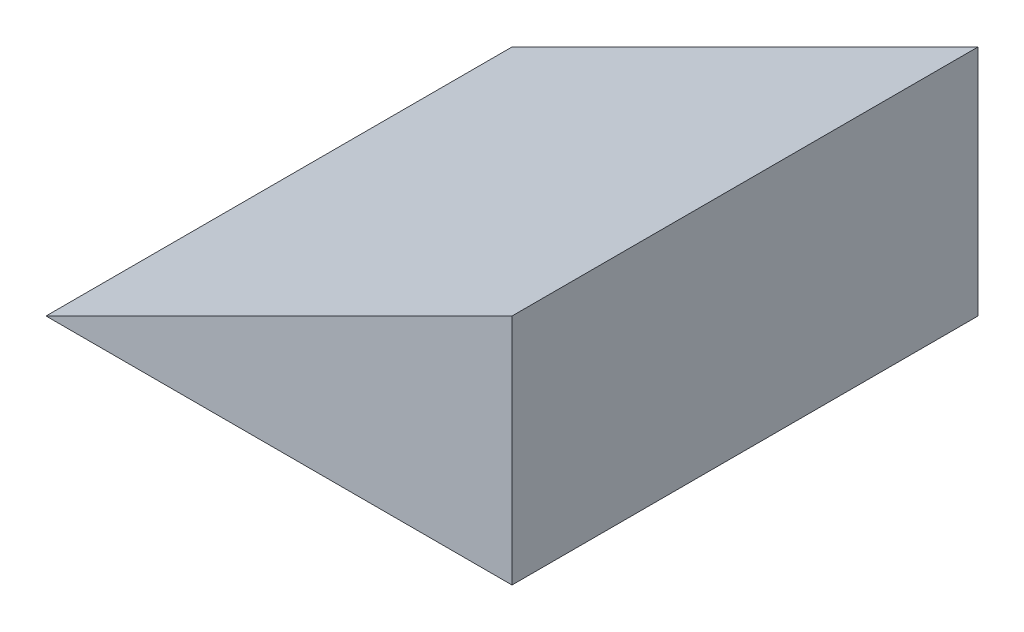
SolidWorks part; units mm, degrees
ref_plane "Płaszczyzna przednia" through (0, 0, 0) normal (0, 0, 1) x (1, 0, 0)
ref_plane "Płaszczyzna górna" through (0, 0, 0) normal (0, 1, 0) x (1, 0, 0)
ref_plane "Płaszczyzna prawa" through (0, 0, 0) normal (1, 0, 0) x (0, 0, -1)
sketch "Szkic1" plane through (0, 0, 0) normal (0, 0, 1) x (1, 0, 0)
  line L0 (-62.645, -30.6962) -> (137.355, -30.6962)
  line L1 (137.355, -30.6962) -> (137.355, 69.3038)
  line L2 (137.355, 69.3038) -> (-62.645, -30.6962)
  dimension "D1" = 200
  dimension "D2" = 100
  dimension "D3" = 223.6068
extrude "Dodanie-wyciągnięcie1" add sketch "Szkic1" along normal blind 200
